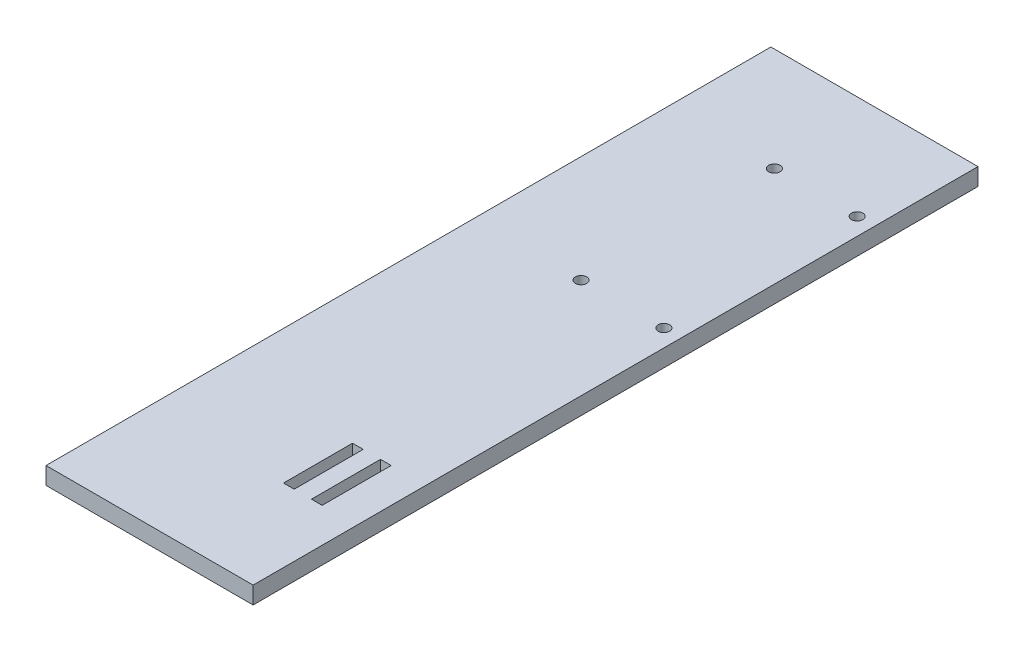
SolidWorks part; units mm, degrees
ref_plane "Front Plane" through (0, 0, 0) normal (0, 0, 1) x (1, 0, 0)
ref_plane "Top Plane" through (0, 0, 0) normal (0, 1, 0) x (1, 0, 0)
ref_plane "Right Plane" through (0, 0, 0) normal (1, 0, 0) x (0, 0, -1)
sketch "Sketch1" plane through (0, 0, 0) normal (0, 1, 0) x (1, 0, 0)
  line L1 (0, 0) -> (60, 0)
  line L2 (0, 0) -> (0, 210)
  line L3 (0, 210) -> (60, 210)
  line L4 (60, 0) -> (60, 210)
  dimension "D1" = 210
  dimension "D2" = 60
extrude "Boss-Extrude1" add sketch "Sketch1" along normal blind 5
sketch "Sketch2" plane through (0, 5, 0) normal (0, 1, 0) x (1, 0, 0)
  line L0 (0, 0) -> (60, 0) construction
  line L1 (46.9, 30) -> (50, 30)
  line L2 (46.9, 30) -> (46.9, 50)
  line L3 (46.9, 50) -> (50, 50)
  line L4 (50, 30) -> (50, 50)
  line L5 (60, 0) -> (60, 210) construction
  line L7 (38.8, 50) -> (41.9, 50)
  line L8 (38.8, 50) -> (38.8, 30)
  line L9 (38.8, 30) -> (41.9, 30)
  line L10 (41.9, 50) -> (41.9, 30)
  dimension "D1" = 3.1
  dimension "D2" = 30
  dimension "D3" = 20
  dimension "D4" = 10
  dimension "D5" = 5
extrude "Cut-Extrude1" cut sketch "Sketch2" against normal blind 5
sketch "Sketch3" plane through (0, 5, 0) normal (0, 1, 0) x (1, 0, 0)
  line L0 (55, 152) -> (31, 152) construction
  line L2 (43, -848) -> (43, 49152) construction
  line L4 (31, 180) -> (55, 180) construction
  line L5 (31, 180) -> (31, 124) construction
  line L6 (31, 124) -> (55, 124) construction
  line L7 (55, 180) -> (55, 124) construction
  line L8 (60, 210) -> (0, 210) construction
  line L9 (60, 0) -> (60, 210) construction
  circle A0 centre (55, 180) radius 1.65
  circle A1 centre (55, 124) radius 1.65
  circle A2 centre (31, 124) radius 1.65
  circle A3 centre (31, 180) radius 1.65
  point P8 (43, 152)
  dimension "D2" = 3.3
  dimension "D1" = 56
  dimension "D3" = 24
  dimension "D4" = 30
  dimension "D5" = 5
extrude "Cut-Extrude2" cut sketch "Sketch3" against normal blind 5
